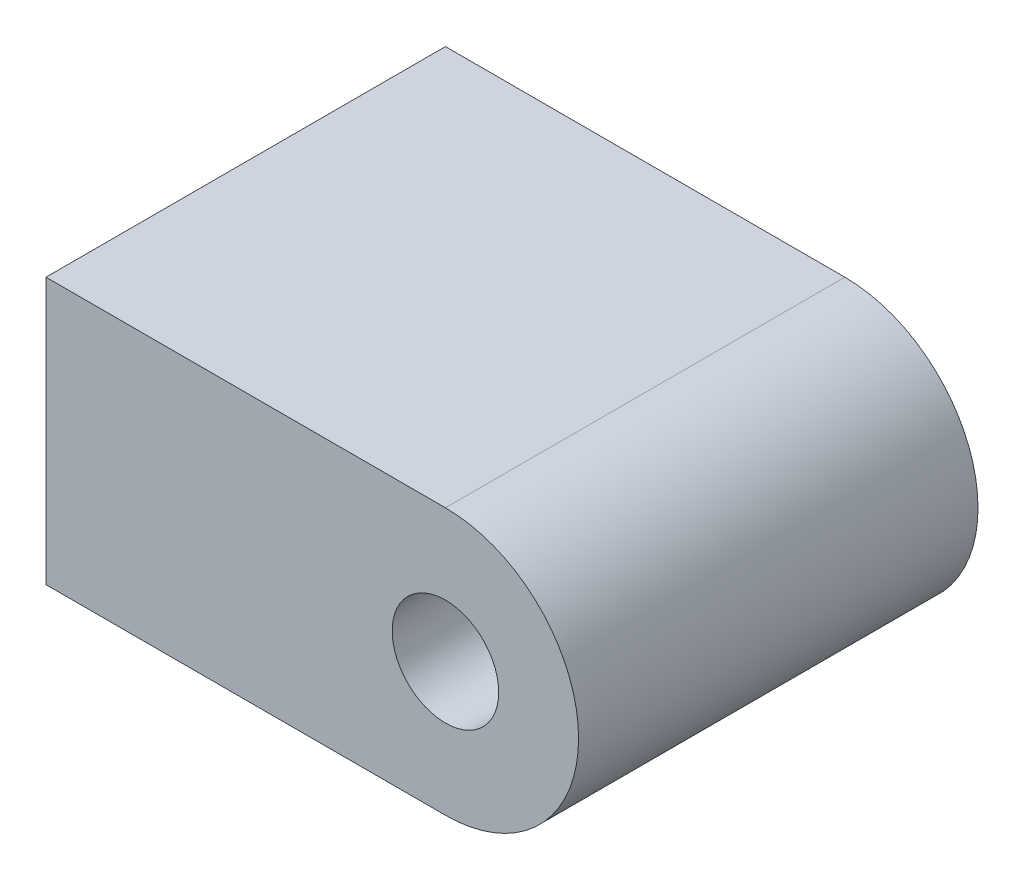
SolidWorks part; units mm, degrees
ref_plane "Front Plane" through (0, 0, 0) normal (0, 0, 1) x (1, 0, 0)
ref_plane "Top Plane" through (0, 0, 0) normal (0, 1, 0) x (1, 0, 0)
ref_plane "Right Plane" through (0, 0, 0) normal (1, 0, 0) x (0, 0, -1)
sketch "Sketch1" plane through (0, 0, 0) normal (0, 0, 1) x (1, 0, 0)
  line L0 (0, 0) -> (150, 0)
  line L1 (150, 0) -> (150, 50)
  line L2 (0, 0) -> (0, 100)
  line L3 (0, 100) -> (150, 100)
  arc A0 (150, 0) -> (150, 100) centre (150, 50) ccw
extrude "Boss-Extrude1" add sketch "Sketch1" along normal blind 150
sketch "Sketch2" plane through (0, 0, 150) normal (0, 0, 1) x (1, 0, 0)
  line L0 (150, 0) -> (150, 50)
  circle A0 centre (150, 50) radius 20
extrude "Cut-Extrude1" cut sketch "Sketch2" against normal blind 150
